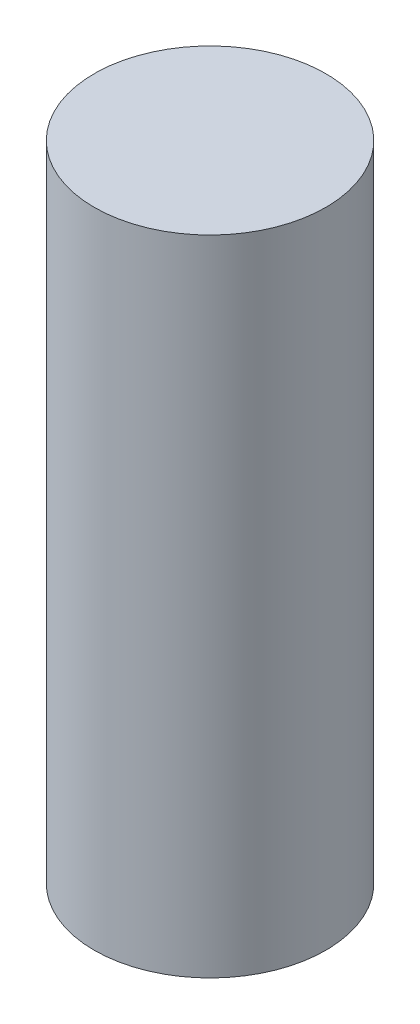
SolidWorks part; units mm, degrees
ref_plane "Front Plane" through (0, 0, 0) normal (0, 0, 1) x (1, 0, 0)
ref_plane "Top Plane" through (0, 0, 0) normal (0, 1, 0) x (1, 0, 0)
ref_plane "Right Plane" through (0, 0, 0) normal (1, 0, 0) x (0, 0, -1)
sketch "Sketch1" plane through (0, 0, 0) normal (0, 1, 0) x (1, 0, 0)
  circle A0 centre (0, 0) radius 1.8
extrude "Boss-Extrude1" add sketch "Sketch1" along normal blind 10
